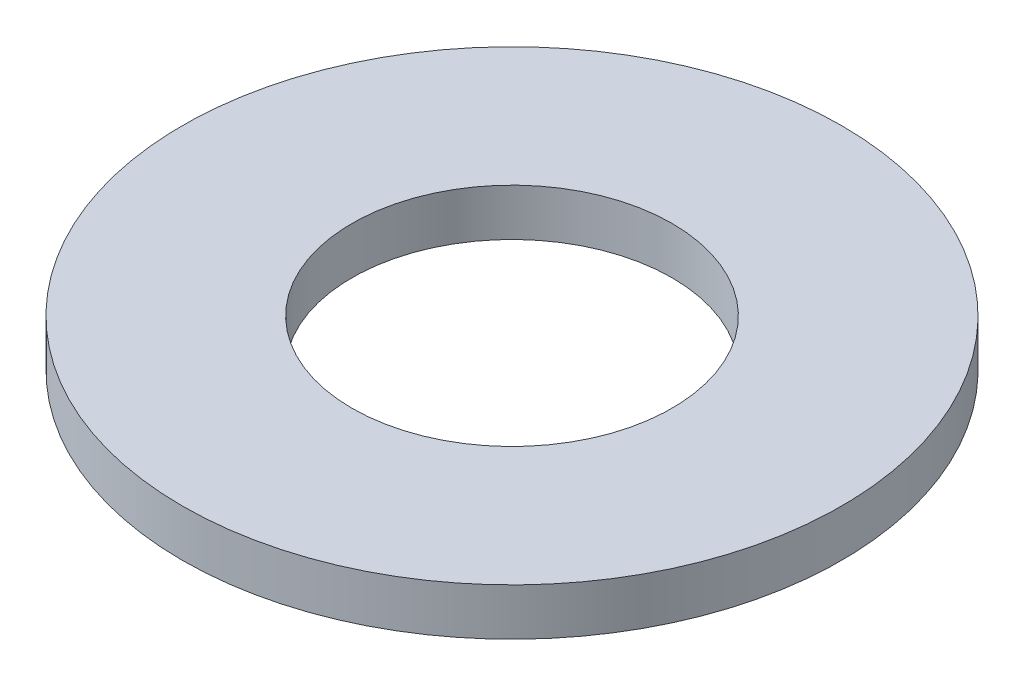
SolidWorks part; units mm, degrees
material "钢"
ref_plane "基准面1" through (0, 0, 0) normal (0, 0, 1) x (1, 0, 0)
ref_plane "基准面2" through (0, 0, 0) normal (0, 1, 0) x (1, 0, 0)
ref_plane "基准面3" through (0, 0, 0) normal (1, 0, 0) x (0, 0, -1)
sketch "尺寸草图" plane through (0, 0, 0) normal (0, 0, 1) x (1, 0, 0)
  line L0 (0, 0) -> (9.1, 0)
  point P3 (0.5, 0)
  point P4 (7, 0)
  point P5 (3.4, 0)
  dimension "h" = 0.5
  dimension "d2" = 7
  dimension "d1" = 3.4
sketch "草图1" plane through (0, 0, 0) normal (0, 0, 1) x (1, 0, 0)
  line L0 (0, 0) -> (0, 52.7318) construction
  line L2 (-1.7, 8.6445) -> (-3.5, 8.6445)
  line L3 (-1.7, 8.6445) -> (-1.7, 9.1445)
  line L4 (-1.7, 9.1445) -> (-3.5, 9.1445)
  line L5 (-3.5, 8.6445) -> (-3.5, 9.1445)
  dimension "h" = 0.5
  dimension "D1" = 1.7
  dimension "D2" = 3.5
revolve "基体-旋转" add sketch "草图1" angle 360 about L0
equation "\"h@草图1\" = \"h@尺寸草图\""
equation "\"D1@草图1\" = \"d1@尺寸草图\" / 2"
equation "\"D2@草图1\" = \"d2@尺寸草图\" / 2"
